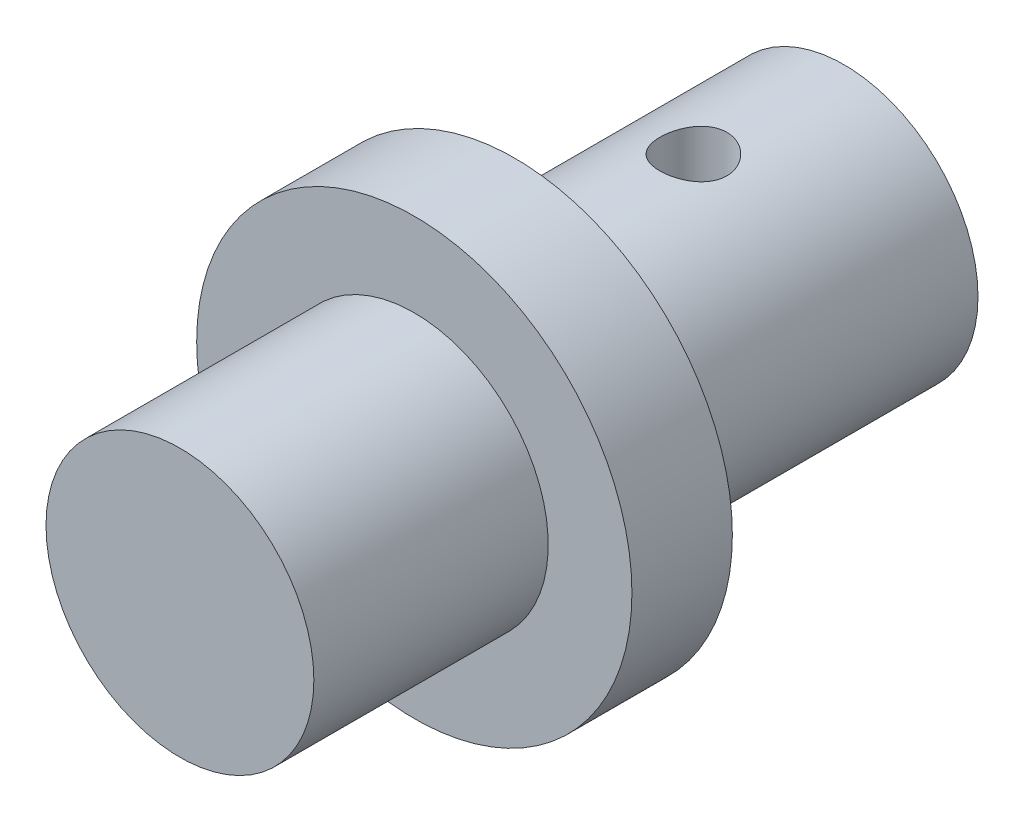
SolidWorks part; units mm, degrees
ref_plane "Front Plane" through (0, 0, 0) normal (0, 0, 1) x (1, 0, 0)
ref_plane "Top Plane" through (0, 0, 0) normal (0, 1, 0) x (1, 0, 0)
ref_plane "Right Plane" through (0, 0, 0) normal (1, 0, 0) x (0, 0, -1)
sketch "Sketch1" plane through (0, 0, 0) normal (0, 0, 1) x (1, 0, 0)
  circle A0 centre (0, 0) radius 4
  dimension "D1" = 8
extrude "Boss-Extrude1" add sketch "Sketch1" along normal blind 19.8358
ref_plane "Plane1" through (0, -4, 0) normal (0, -1, 0) x (-1, 0, 0)
sketch "Sketch3" plane through (0, -4, 0) normal (0, -1, 0) x (-1, 0, 0)
  line L0 (-4, 0) -> (4, -9) construction
  line L1 (4, -19.8358) -> (4, 0) construction
  line L2 (4, 0) -> (-4, -9) construction
  line L3 (-4, 0) -> (-4, -19.8358) construction
  circle A0 centre (0, -4.5) radius 1
  dimension "D2" = 2
  dimension "D1" = 9
extrude "Cut-Extrude1" cut sketch "Sketch3" against normal through all
sketch "Sketch4" plane through (0, -4, 0) normal (0, -1, 0) x (-1, 0, 0)
  circle A0 centre (0, -4.5) radius 2.475
  dimension "D1" = 4.95
extrude "Cut-Extrude2" cut sketch "Sketch4" against normal blind 2.5852
ref_plane "Plane2" through (0, 0, 12.8359) normal (0, 0, -1) x (-1, 0, 0)
sketch "Sketch5" plane through (0, 0, 12.8359) normal (0, 0, -1) x (-1, 0, 0)
  circle A0 centre (0, 0) radius 6.5
  circle A1 centre (0, 0) radius 4 construction
  circle A2 centre (0, 0) radius 4
  dimension "D1" = 13
extrude "Boss-Extrude2" add sketch "Sketch5" along normal blind 3
